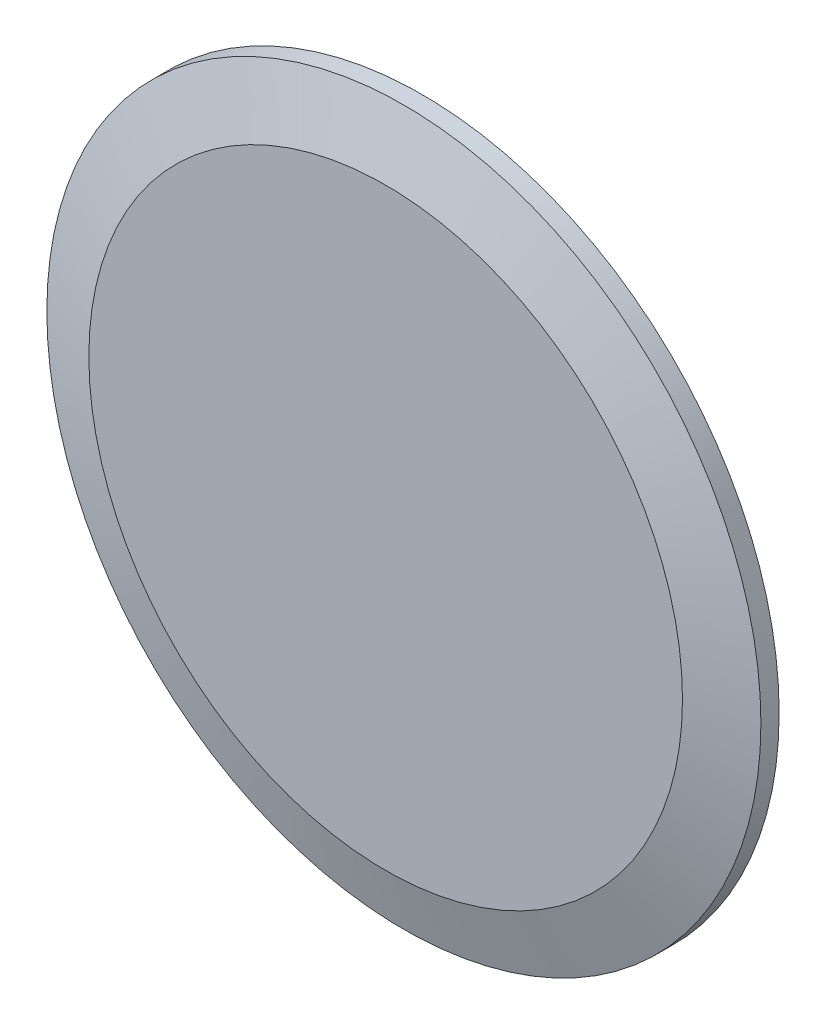
SolidWorks part; units mm, degrees
ref_plane "Plan de face" through (0, 0, 0) normal (0, 0, 1) x (1, 0, 0)
ref_plane "Plan de dessus" through (0, 0, 0) normal (0, 1, 0) x (1, 0, 0)
ref_plane "Plan de droite" through (0, 0, 0) normal (1, 0, 0) x (0, 0, -1)
sketch "Contour" plane through (0, 0, 0) normal (0, 0, 1) x (1, 0, 0)
  circle A0 centre (0, 0) radius 21.05
  dimension "D1" = 42.1
extrude "Boss.-Extru.1_Contour" add sketch "Contour" along normal blind 2.15
ref_axis "Axe1" through (0, 0, -0.1075) along (0, 0, 1)
sketch "Chanfrein_Bordure" plane through (0, 0, 0) normal (0, 1, 0) x (1, 0, 0)
  line L0 (17.5, -2.15) -> (21.05, -1.075)
  line L1 (-21.05, -2.15) -> (21.05, -2.15) construction
  line L2 (21.05, -2.15) -> (21.05, 0) construction
  line L3 (21.05, -1.075) -> (21.05, -2.15)
  line L4 (21.05, -2.15) -> (17.5, -2.15)
  line L5 (21.05, 0) -> (21.05, -2.15) construction
  line L7 (21.05, 0) -> (-21.05, 0) construction
  point P15 (21.05, -1.075)
  dimension "D1" = 3.55
revolve "Enlèvement de matière-Révolution1" cut sketch "Chanfrein_Bordure" angle 360 about axis through (0, 0, -0.1075) along (0, 0, 1)
